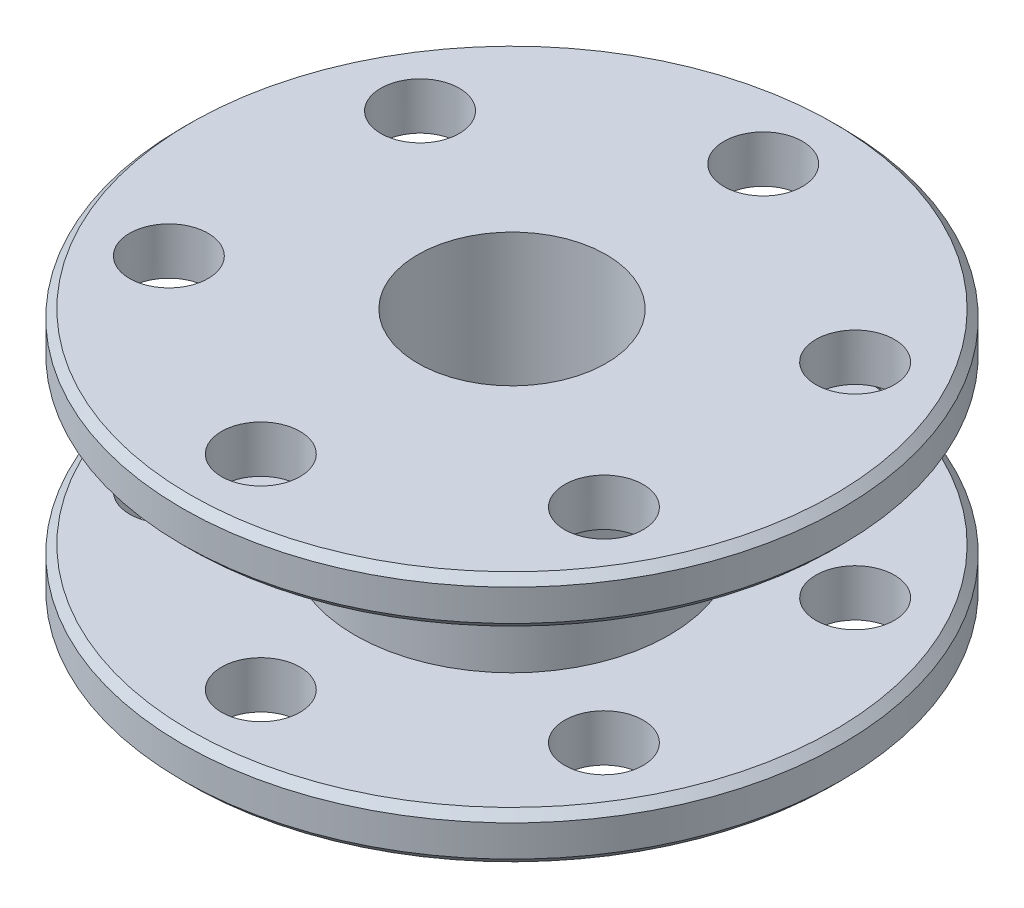
SolidWorks part; units mm, degrees
ref_plane "Front Plane" through (0, 0, 0) normal (0, 0, 1) x (1, 0, 0)
ref_plane "Top Plane" through (0, 0, 0) normal (0, 1, 0) x (1, 0, 0)
ref_plane "Right Plane" through (0, 0, 0) normal (1, 0, 0) x (0, 0, -1)
sketch "Sketch1" plane through (0, 0, 0) normal (0, 0, 1) x (1, 0, 0)
  line L0 (6, 0) -> (6, 16)
  line L1 (6, 16) -> (21, 16)
  line L2 (21, 16) -> (21, 13)
  line L3 (21, 13) -> (10, 13)
  line L4 (10, 13) -> (10, 3)
  line L5 (10, 3) -> (21, 3)
  line L6 (21, 3) -> (21, 0)
  line L7 (21, 0) -> (6, 0)
  line L8 (0, 0) -> (0, 16.6538) construction
  dimension "D1" = 6
  dimension "D2" = 10
  dimension "D3" = 21
  dimension "D4" = 3
  dimension "D5" = 16
revolve "Revolve1" add sketch "Sketch1" angle 360 about L8
chamfer "Chamfer1" distance 0.5 angle 45 4 edges at (0, 16, -21) (0, 13, -21) (0, 3, -21) (0, 0, -21)
sketch "Sketch2" plane through (0, 16, 0) normal (0, 1, 0) x (1, 0, 0)
  circle A0 centre (0, 0) radius 16 construction
  circle A1 centre (0, 16) radius 2.5
  circle A2 centre (13.8564, 8) radius 2.5
  circle A3 centre (13.8564, -8) radius 2.5
  circle A4 centre (0, -16) radius 2.5
  circle A5 centre (-13.8564, -8) radius 2.5
  circle A6 centre (-13.8564, 8) radius 2.5
  point P18 (0, 0)
  dimension "D1" = 32
  dimension "D2" = 5
  dimension "D3" = 6
extrude "Cut-Extrude1" cut sketch "Sketch2" against normal through all
